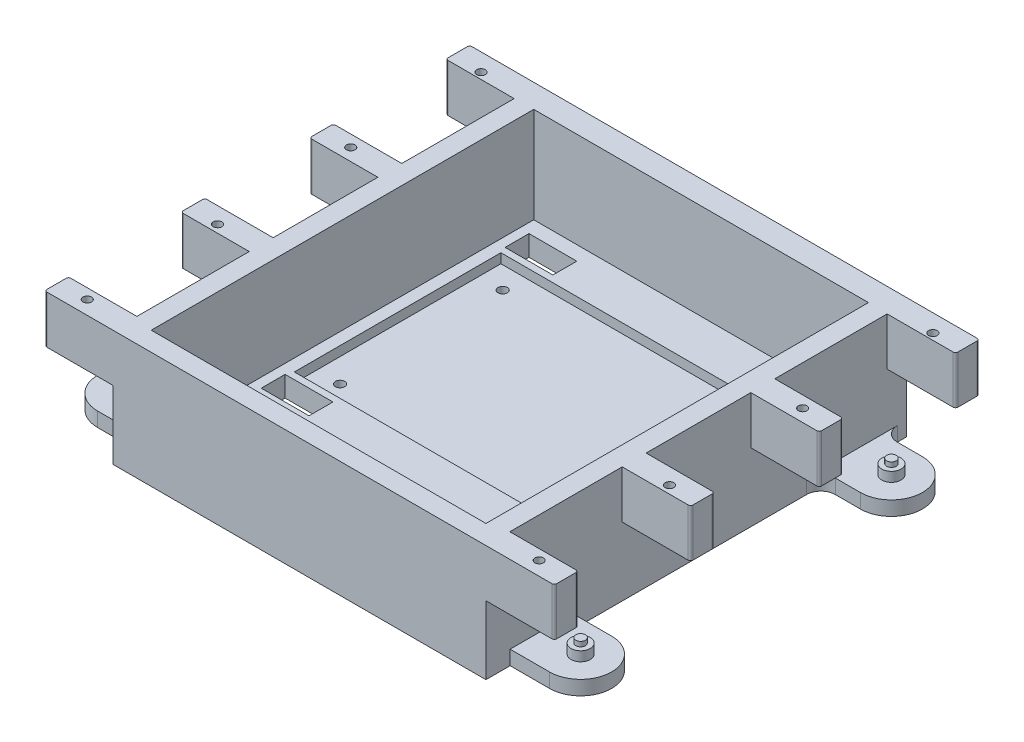
SolidWorks part; units mm, degrees
material "聚脂树脂"
ref_plane "前视基准面" through (0, 0, 0) normal (0, 0, 1) x (1, 0, 0)
ref_plane "上视基准面" through (0, 0, 0) normal (0, 1, 0) x (1, 0, 0)
ref_plane "右视基准面" through (0, 0, 0) normal (1, 0, 0) x (0, 0, -1)
sketch "草图1" plane through (0, 0, 0) normal (0, 1, 0) x (1, 0, 0)
  line L1 (-39, -44) -> (39, -44)
  line L2 (-39, -44) -> (-39, 44)
  line L3 (-39, 44) -> (39, 44)
  line L4 (39, -44) -> (39, 44)
  line L5 (-39, -44) -> (39, 44) construction
  line L6 (-39, 44) -> (39, -44) construction
  line L7 (-35, -40) -> (35, -40)
  line L8 (-35, -40) -> (-35, 40)
  line L9 (-35, 40) -> (35, 40)
  line L10 (35, -40) -> (35, 40)
  line L11 (-35, -40) -> (35, 40) construction
  line L12 (-35, 40) -> (35, -40) construction
  point P0 (0, 0)
  point P6 (0, 0)
  dimension "D1" = 4
  dimension "D2" = 4
  dimension "D3" = 70
  dimension "D4" = 80
extrude "凸台-拉伸1" add sketch "草图1" along normal blind 10
sketch "草图2" plane through (0, 0, 0) normal (0, -1, 0) x (1, 0, 0)
  line L1 (-39, 44) -> (39, 44)
  line L2 (-39, 44) -> (-39, -44)
  line L3 (-39, -44) -> (39, -44)
  line L4 (39, 44) -> (39, -44)
extrude "凸台-拉伸3" add sketch "草图2" along normal blind 14.3
sketch "草图3" plane through (-39, 0, 0) normal (-1, 0, 0) x (0, 0, 1)
  line L0 (-44, 10) -> (44, 10) construction
  line L1 (44, 10) -> (39, 10)
  line L2 (44, 10) -> (44, 0)
  line L3 (44, 0) -> (39, 0)
  line L4 (39, 10) -> (39, 0)
  line L5 (15.5, 10) -> (10.5, 10)
  line L6 (15.5, 10) -> (15.5, 0)
  line L7 (15.5, 0) -> (10.5, 0)
  line L8 (10.5, 10) -> (10.5, 0)
  dimension "D1" = 5
  dimension "D2" = 5
  dimension "D3" = 10
  dimension "D4" = 10
  dimension "D5" = 23.5
extrude "凸台-拉伸4" add sketch "草图3" along normal blind 14.3
pattern_linear "阵列(线性)2" count 2 spacing 55.4 along (0, 0, -1) of "凸台-拉伸4"
mirror "镜向3" about plane through (0, 0, 0) normal (1, 0, 0) of "阵列(线性)2", "凸台-拉伸4"
sketch "草图7" plane through (0, 0, 0) normal (0, 1, 0) x (1, 0, 0)
  line L4 (-35, 40) -> (-35, -40)
  line L5 (-35, -40) -> (35, -40)
  line L6 (35, -40) -> (35, 40)
  line L7 (35, 40) -> (-35, 40)
  line L8 (-35, 40) -> (-35, -40)
  line L9 (-35, -40) -> (35, -40)
  line L10 (35, -40) -> (35, 40)
  line L11 (35, 40) -> (-35, 40)
  dimension "D1" = 0
extrude "切除-拉伸1" cut sketch "草图7" against normal blind 10
sketch "草图8" plane through (0, -14.3, 0) normal (0, -1, 0) x (1, 0, 0)
  line L0 (39, -44) -> (39, 44) construction
  line L1 (47.25, -26.06) -> (39, -26.06)
  line L4 (39, -26.06) -> (39, -38.5598)
  line L5 (47.25, -39.04) -> (39, -39.04)
  line L6 (39, -38.5598) -> (39, -39.04)
  arc A2 (47.25, -39.04) -> (47.25, -26.06) centre (47.25, -32.55) ccw
  dimension "D1" = 8.25
sketch "草图12" plane through (0, -14.3, 0) normal (0, -1, 0) x (1, 0, 0)
  line L0 (-39, -44) -> (0, -49.5709)
  line L1 (0, -49.5709) -> (39, -44)
  line L2 (39, -44) -> (-39, -44)
extrude "凸台-拉伸9" add sketch "草图12" against normal up to vertex (14.3 mm away)
fillet "圆角1" radius 0.5 16 edges at (-53.3, 5, 15.5) (-53.3, 5, 10.5) (-53.3, 5, 44) (-53.3, 5, 39) (53.3, 5, 44) (53.3, 5, 39) (53.3, 5, 15.5) (53.3, 5, 10.5) (53.3, 5, -16.4) (53.3, 5, -11.4) (53.3, 5, -39.9) (53.3, 5, -44.9) (-53.3, 5, -11.4) (-53.3, 5, -39.9) (-53.3, 5, -16.4) (-53.3, 5, -44.9)
sketch "草图13" plane through (0, -14.3, 0) normal (0, -1, 0) x (1, 0, 0)
  line L0 (0, -49.5709) -> (0, 49.5403) construction
  line L2 (-33, -32) -> (-23, -32)
  line L3 (-33, -32) -> (-33, -37)
  line L4 (-33, -37) -> (-23, -37)
  line L5 (-23, -32) -> (-23, -37)
  line L6 (-33, 19) -> (-23, 19)
  line L7 (-33, 19) -> (-33, 14)
  line L8 (-33, 14) -> (-23, 14)
  line L9 (-23, 19) -> (-23, 14)
  line L10 (23, -32) -> (23, -37)
  line L11 (33, -37) -> (23, -37)
  line L12 (33, -32) -> (33, -37)
  line L13 (33, -32) -> (23, -32)
  line L14 (23, 19) -> (23, 14)
  line L15 (33, 14) -> (23, 14)
  line L16 (33, 19) -> (33, 14)
  line L17 (33, 19) -> (23, 19)
  line L22 (-35, -40) -> (35, -40)
  line L23 (-35, 40) -> (-35, -40)
  line L24 (35, 40) -> (-35, 40)
  line L25 (35, -40) -> (35, 40)
  line L26 (-35, -40) -> (35, -40) construction
  line L27 (-35, 40) -> (-35, -40) construction
  line L28 (35, 40) -> (-35, 40) construction
  line L29 (35, -40) -> (35, 40) construction
  dimension "D1" = 10
  dimension "D2" = 5
  dimension "D4" = 2
  dimension "D5" = 3
  dimension "D6" = 21
  dimension "D3" = 0
extrude "切除-拉伸2" cut sketch "草图13" against normal up to next
extrude "凸台-拉伸11" add sketch "草图8" against normal blind 3
sketch "草图14" plane through (0, -11.3, 0) normal (0, 1, 0) x (1, 0, 0)
  circle A0 centre (47.25, 32.55) radius 2
  dimension "D1" = 4
extrude "凸台-拉伸12" add sketch "草图14" along normal blind 2
sketch "草图15" plane through (0, -9.3, 0) normal (0, 1, 0) x (1, 0, 0)
  circle A0 centre (47.25, 32.55) radius 1
  dimension "D1" = 2
extrude "凸台-拉伸13" add sketch "草图15" along normal blind 1
mirror "镜向4" about plane through (0, 0, 0) normal (1, 0, 0) of "凸台-拉伸13", "凸台-拉伸12", "凸台-拉伸11"
pattern_linear "阵列(线性)3" count 2 spacing 65 along (0, 0, 1) of "凸台-拉伸11", "凸台-拉伸12", "凸台-拉伸13", "镜向4"
sketch "草图16" plane through (0, 0, -44) normal (0, 0, -1) x (-1, 0, 0)
  line L4 (-39, 0) -> (39, 0)
  line L5 (39, 0) -> (39, 10)
  line L6 (39, 10) -> (-39, 10)
  line L7 (-39, 10) -> (-39, 0)
  line L8 (-39, 0) -> (39, 0)
  line L9 (39, 0) -> (39, 10)
  line L10 (39, 10) -> (-39, 10)
  line L11 (-39, 10) -> (-39, 0)
  dimension "D1" = 0
extrude "凸台-拉伸14" add sketch "草图16" along normal blind 0.9
sketch "草图18" plane through (0, -10, 0) normal (0, 1, 0) x (1, 0, 0)
  line L0 (-31.5, 28) -> (-31.5, -10) construction
  line L1 (-29.5, -12) -> (24.5, -12) construction
  line L2 (26.5, -10) -> (26.5, 28) construction
  line L3 (24.5, 30) -> (-29.5, 30) construction
  line L4 (-31.5, 28) -> (-31.5, -10)
  line L5 (-29.5, -12) -> (24.5, -12)
  line L6 (26.5, -10) -> (26.5, 28)
  line L7 (24.5, 30) -> (-29.5, 30)
  arc A0 (-29.5, 30) -> (-31.5, 28) centre (-29.5, 28) ccw construction
  arc A1 (-31.5, -10) -> (-29.5, -12) centre (-29.5, -10) ccw construction
  arc A2 (24.5, -12) -> (26.5, -10) centre (24.5, -10) ccw construction
  arc A3 (26.5, 28) -> (24.5, 30) centre (24.5, 28) ccw construction
  arc A4 (-29.5, 30) -> (-31.5, 28) centre (-29.5, 28) ccw
  arc A5 (-31.5, -10) -> (-29.5, -12) centre (-29.5, -10) ccw
  arc A6 (24.5, -12) -> (26.5, -10) centre (24.5, -10) ccw
  arc A7 (26.5, 28) -> (24.5, 30) centre (24.5, 28) ccw
extrude "切除-拉伸3" cut sketch "草图18" against normal blind 2
sketch "草图19" plane through (0, -12, 0) normal (0, 1, 0) x (1, 0, 0)
  circle A0 centre (22.5, 26) radius 0.9782
  circle A1 centre (22.5, -8) radius 0.9782
  circle A2 centre (-27.5, -8) radius 0.9782
  circle A3 centre (-27.5, 26) radius 0.9782
extrude "切除-拉伸4" cut sketch "草图19" against normal through all
sketch "草图20" plane through (0, -12, 0) normal (0, 1, 0) x (1, 0, 0)
  line L0 (-2.5, 30) -> (-2.5, -12) construction
  line L1 (24.5, 30) -> (-29.5, 30) construction
  line L2 (-29.5, -12) -> (24.5, -12) construction
  line L3 (26.5, 9) -> (-31.5, 9) construction
  line L4 (26.5, -10) -> (26.5, 28) construction
  line L5 (-31.5, 28) -> (-31.5, -10) construction
  line L7 (-32.4724, -12.5975) -> (27.4724, -12.5975)
  line L8 (-32.4724, -12.5975) -> (-32.4724, 30.5975)
  line L9 (-32.4724, 30.5975) -> (27.4724, 30.5975)
  line L10 (27.4724, -12.5975) -> (27.4724, 30.5975)
  line L11 (-32.4724, -12.5975) -> (27.4724, 30.5975) construction
  line L12 (-32.4724, 30.5975) -> (27.4724, -12.5975) construction
  point P12 (-2.5, 9)
  point P17 (-2.5, 9)
extrude "切除-拉伸5" cut sketch "草图20" along normal blind 2
fillet "圆角2" radius 3 6 edges at (-39, -12.8, 25.96) (-39, -12.8, 38.94) (-39, -12.8, -26.06) (-39, -12.8, -39.04) (39, -12.8, -39.04) (39, -12.8, -26.06)
sketch "草图23" plane through (0, 10, 0) normal (0, 1, 0) x (1, 0, 0)
  circle A0 centre (-47.25, -41.122) radius 0.9 construction
  circle A1 centre (-47.25, -13.878) radius 0.9 construction
  circle A2 centre (-47.25, 13.978) radius 0.9 construction
  circle A3 centre (-47.25, 41.222) radius 0.9 construction
  circle A4 centre (47.25, -41.122) radius 0.9 construction
  circle A5 centre (47.25, -13.878) radius 0.9 construction
  circle A6 centre (47.25, 13.978) radius 0.9 construction
  circle A7 centre (47.25, 41.222) radius 0.9 construction
  circle A8 centre (-47.25, -41.122) radius 0.9
  circle A9 centre (-47.25, -13.878) radius 0.9
  circle A10 centre (-47.25, 13.978) radius 0.9
  circle A11 centre (-47.25, 41.222) radius 0.9
  circle A12 centre (47.25, -41.122) radius 0.9
  circle A13 centre (47.25, -13.878) radius 0.9
  circle A14 centre (47.25, 13.978) radius 0.9
  circle A15 centre (47.25, 41.222) radius 0.9
extrude "切除-拉伸8" cut sketch "草图23" against normal blind 2
